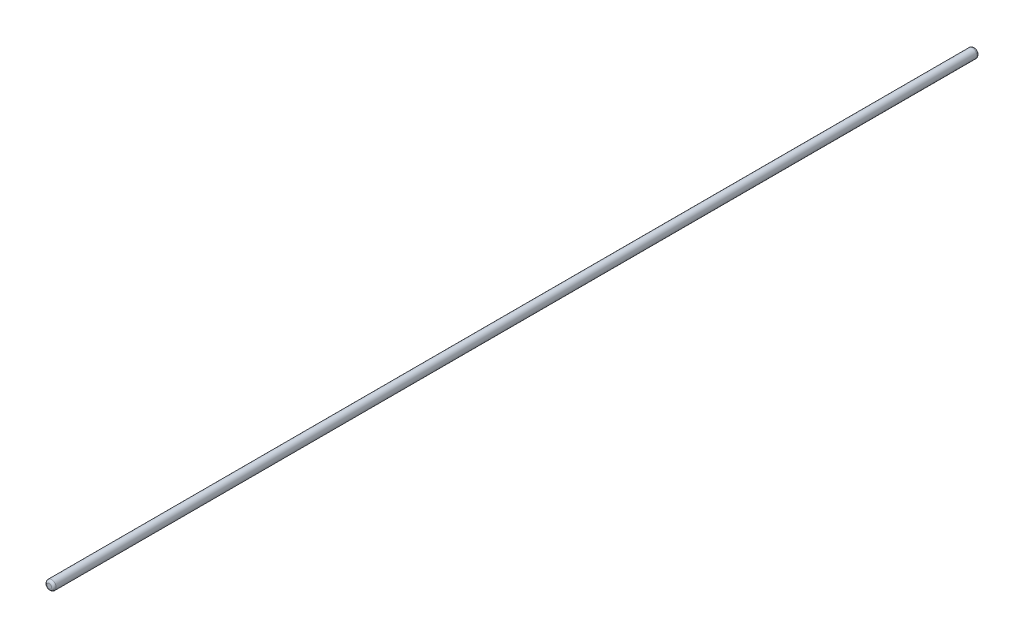
SolidWorks part; units mm, degrees
ref_plane "Front Plane" through (0, 0, 0) normal (1, 0, 0) x (0, 1, 0)
ref_plane "Top Plane" through (0, 0, 0) normal (0, 0, 1) x (0, 1, 0)
ref_plane "Right Plane" through (0, 0, 0) normal (0, 1, 0) x (-1, 0, 0)
sketch "Sketch1" plane through (0, 0, 0) normal (0, 0, 1) x (0, 1, 0)
  circle A0 centre (0, 0) radius 1.5
  dimension "D1" = 3
extrude "Boss-Extrude1" add sketch "Sketch1" along normal blind 300
fillet "Fillet1" radius 0.75 2 edges at (1.5, 0, 0) (1.5, 0, 300)
